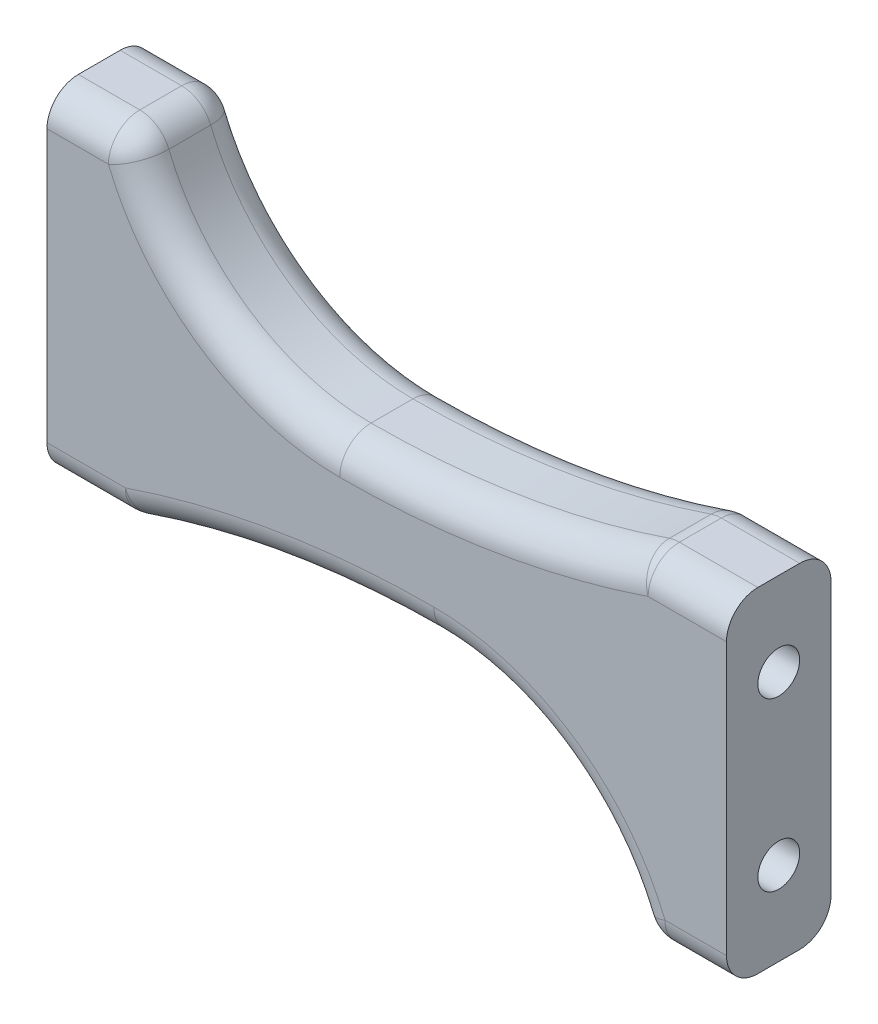
SolidWorks part; units mm, degrees
material "Mahogany"
ref_plane "Front" through (0, 0, 0) normal (0, 0, 1) x (1, 0, 0)
ref_plane "Top" through (0, 0, 0) normal (0, 1, 0) x (1, 0, 0)
ref_plane "Right" through (0, 0, 0) normal (1, 0, 0) x (0, 0, -1)
sketch "Sketch1" plane through (0, 0, 0) normal (0, 0, 1) x (1, 0, 0)
  line L0 (0, 32) -> (0, 0)
  line L1 (0, 0) -> (8, 0)
  line L2 (57, -10) -> (65, -10)
  line L3 (65, -10) -> (65, 22)
  line L4 (65, 22) -> (57, 22)
  line L5 (8, 32) -> (0, 32)
  arc A6 (57, 22) -> (28, 17.1194) centre (28, 105.7169) cw
  arc A7 (28, 17.1194) -> (8, 32) centre (28, 38) cw
  arc A8 (8, 0) -> (37, 4.8806) centre (37, -83.7169) cw
  arc A9 (37, 4.8806) -> (57, -10) centre (37, -16) cw
  point P10 (4, 32)
  dimension "D1" = 32
  dimension "D2" = 10
  dimension "D3" = 65
  dimension "D4" = 8
  dimension "D5" = 37
  dimension "D6" = 37
  dimension "D7" = 16
  dimension "D8" = 16
extrude "Boss-Extrude1" add sketch "Sketch1" along normal mid plane 10
sketch "Sketch2" plane through (65, 0, 0) normal (1, 0, 0) x (0, 0, -1)
  line L0 (-5, -10) -> (5, -10) construction
  circle A0 centre (0, -2) radius 2
  circle A1 centre (0, 14) radius 2
  dimension "D3" = 4
  dimension "D1" = 8
  dimension "D2" = 24
extrude "Cut-Extrude1" cut sketch "Sketch2" against normal blind 7
sketch "Sketch3" plane through (0, 0, 0) normal (-1, 0, 0) x (0, 0, 1)
  line L0 (5, 0) -> (-5, 0) construction
  circle A0 centre (0, 8) radius 2
  circle A1 centre (0, 24) radius 2
  dimension "D1" = 4
  dimension "D2" = 8
  dimension "D3" = 24
extrude "Cut-Extrude2" cut sketch "Sketch3" against normal blind 7
fillet "Fillet1" radius 3 20 edges at (15.5357, 21.2476, 5) (42.7039, 18.3481, 5) (61, 22, 5) (61, -10, 5) (49.4643, 0.7524, 5) (22.2961, 3.6519, 5) (4, 0, 5) (4, 32, 5) (4, 0, -5) (22.2961, 3.6519, -5) (49.4643, 0.7524, -5) (61, -10, -5) (61, 22, -5) (42.7039, 18.3481, -5) (15.5357, 21.2476, -5) (4, 32, -5) (57, -10, 0) (8, 32, 0) (57, 22, 0) (8, 0, 0)
